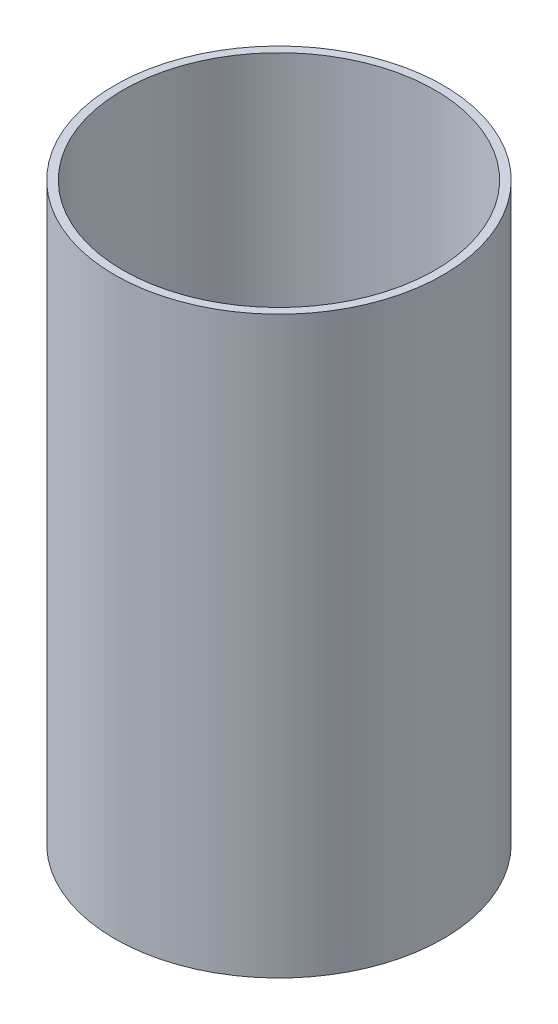
SolidWorks part; units mm, degrees
ref_plane "Front Plane" through (0, 0, 0) normal (0, 0, 1) x (1, 0, 0)
ref_plane "Top Plane" through (0, 0, 0) normal (0, 1, 0) x (1, 0, 0)
ref_plane "Right Plane" through (0, 0, 0) normal (1, 0, 0) x (0, 0, -1)
sketch "Sketch1" plane through (0, 0, 0) normal (0, 1, 0) x (1, 0, 0)
  circle A0 centre (0, 0) radius 50.8
  circle A1 centre (0, 0) radius 48.26
  dimension "D1" = 101.6
  dimension "D2" = 2.54
extrude "Boss-Extrude1" add sketch "Sketch1" along normal blind 177.8
